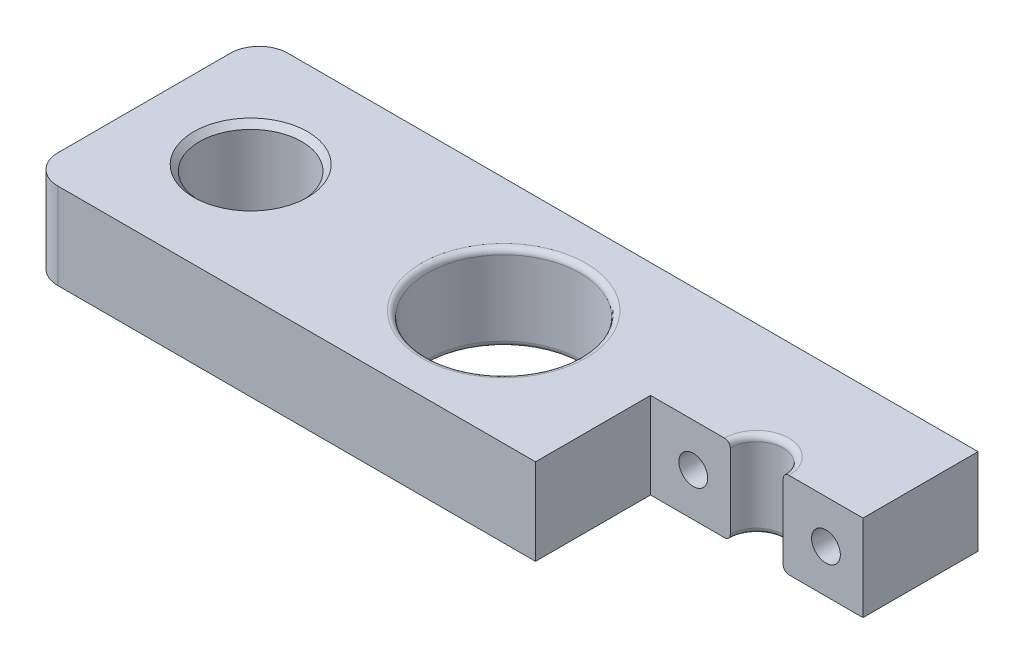
SolidWorks part; units mm, degrees
ref_plane "前基準面" through (0, 0, 0) normal (0, 0, 1) x (1, 0, 0)
ref_plane "上基準面" through (0, 0, 0) normal (0, 1, 0) x (1, 0, 0)
ref_plane "右基準面" through (0, 0, 0) normal (1, 0, 0) x (0, 0, -1)
sketch "草圖1" plane through (0, 0, 0) normal (0, 1, 0) x (1, 0, 0)
  line L1 (0, 0) -> (125, 0)
  line L2 (0, 0) -> (0, 40)
  line L3 (0, 40) -> (125, 40)
  line L4 (125, 0) -> (125, 40)
  dimension "D1" = 125
  dimension "D2" = 40
extrude "填料-伸長1" add sketch "草圖1" along normal blind 15
sketch "草圖2" plane through (0, 15, 0) normal (0, 1, 0) x (1, 0, 0)
  line L0 (-4.3311, 20) -> (135.7424, 20) construction
  line L1 (0, 0) -> (125, 0) construction
  line L2 (125, 40) -> (0, 40) construction
  line L3 (0, 40) -> (0, 0) construction
  circle A0 centre (18.5267, 20) radius 8.9
  circle A1 centre (106.5267, 20) radius 4.6
  circle A2 centre (62.5267, 20) radius 13.3
  dimension "D1" = 26.6
  dimension "D2" = 9.2
  dimension "D3" = 17.8
  dimension "D4" = 44
  dimension "D5" = 44
  dimension "D6" = 18.5267
extrude "除料-伸長1" cut sketch "草圖2" against normal through all
chamfer "導角1" distance 1 angle 45 1 edges at (18.5267, 15, -11.1)
chamfer "導角2" distance 1 angle 45 1 edges at (18.5267, 0, -11.1)
fillet "圓角1" radius 1 4 edges at (62.5267, 0, -6.7) (106.5267, 0, -15.4) (106.5267, 15, -15.4) (62.5267, 15, -6.7)
sketch "草圖5" plane through (0, 15, 0) normal (0, 1, 0) x (1, 0, 0)
  line L0 (85, 20) -> (125, 20)
  line L1 (125, 0) -> (85, 0)
  line L2 (125, 0) -> (125, 20)
  line L4 (85, 0) -> (85, 20)
  dimension "D1" = 40
extrude "除料-伸長2" cut sketch "草圖5" against normal through all
fillet "圓角4" radius 5 2 edges at (0, 7.5, -40) (0, 7.5, 0)
sketch "草圖12" plane through (0, 15, 0) normal (0, 1, 0) x (1, 0, 0)
  line L0 (5, 0) -> (85, 0) construction
  line L1 (85, 20) -> (88.06, 20)
  line L2 (85, 20) -> (85, 0)
  line L3 (85, 0) -> (88.06, 0)
  line L4 (88.06, 20) -> (88.06, 0)
  point P5 (88.06, 1.1273)
  dimension "D1" = 3.06
extrude "填料-伸長2" add sketch "草圖12" against normal up to surface (15 mm away) up to face at (64.0982, 0, -20.56)
sketch "草圖14" plane through (0, 0, -20) normal (0, 0, 1) x (1, 0, 0)
  line L0 (100.9267, 0) -> (88.06, 0) construction
  line L1 (125, 0) -> (112.1267, 0) construction
  line L3 (125, 0) -> (125, 15) construction
  line L4 (101.9267, 14) -> (101.9267, 1) construction
  circle A0 centre (118.565, 7.5) radius 2.5
  circle A1 centre (95.4917, 7.5) radius 2.5
  dimension "D1" = 5
  dimension "D2" = 5
  dimension "D5" = 6.435
  dimension "D3" = 7.5
  dimension "D4" = 7.5
  dimension "D6" = 6.435
extrude "除料-伸長3" cut sketch "草圖14" against normal through all
